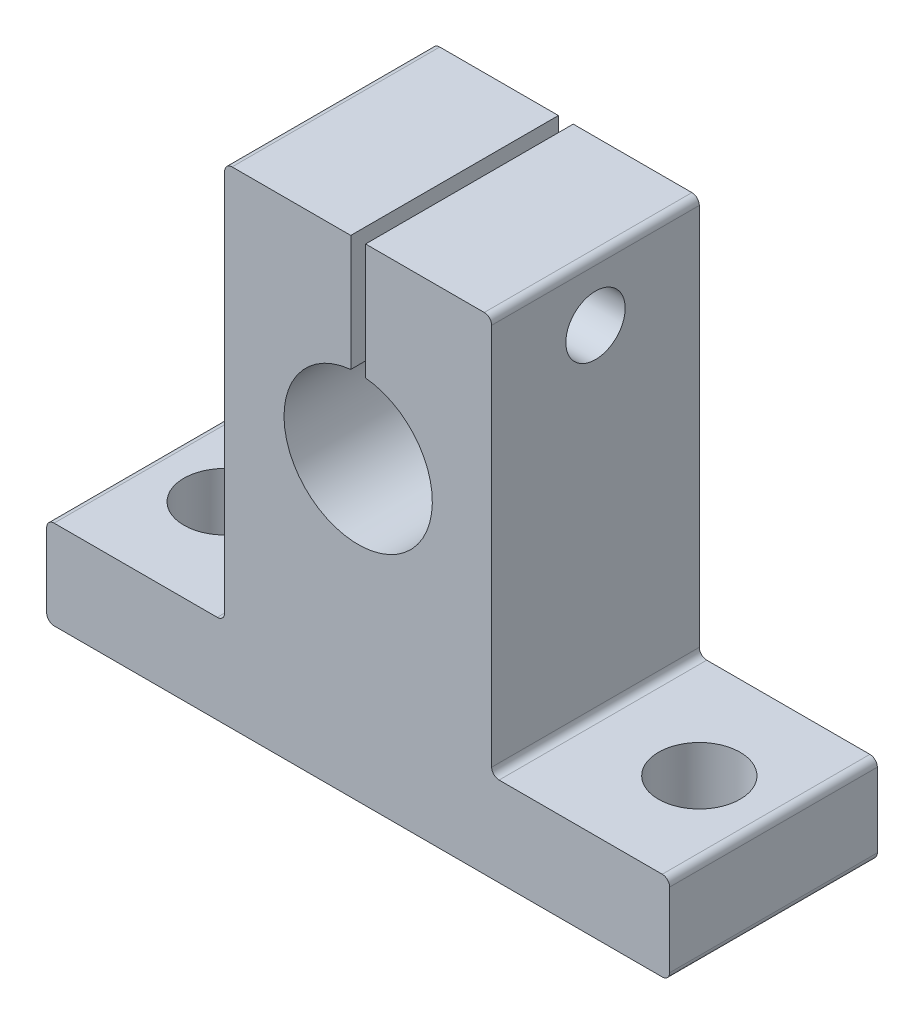
SolidWorks part; units mm, degrees
ref_plane "Front Plane" through (0, 0, 0) normal (0, 0, 1) x (1, 0, 0)
ref_plane "Top Plane" through (0, 0, 0) normal (0, 1, 0) x (1, 0, 0)
ref_plane "Right Plane" through (0, 0, 0) normal (1, 0, 0) x (0, 0, -1)
sketch "Sketch1" plane through (0, 0, 0) normal (0, 0, 1) x (1, 0, 0)
  line L0 (0, 13.4) -> (0, -19.4) construction
  line L1 (-9, -13.4) -> (9, -13.4) construction
  line L2 (-9, -13.4) -> (-9, 13.4)
  line L3 (-9, 13.4) -> (-0.5, 13.4)
  line L4 (9, -13.4) -> (9, 13.4)
  line L5 (-9, -13.4) -> (9, 13.4) construction
  line L6 (-9, 13.4) -> (9, -13.4) construction
  line L7 (-9, -13.4) -> (-21, -13.4)
  line L8 (-21, -13.4) -> (-21, -19.4)
  line L9 (-21, -19.4) -> (21, -19.4)
  line L10 (21, -13.4) -> (21, -19.4)
  line L11 (9, -13.4) -> (21, -13.4)
  line L12 (-0.5, 13.4) -> (-0.5, 5.5749)
  line L13 (0.5, 13.4) -> (0.5, 5.5749)
  line L14 (0.5, 13.4) -> (9, 13.4)
  arc A0 (-0.5, 5.5749) -> (0.5, 5.5749) centre (0, 0.6) ccw
  point P0 (0, 0)
  dimension "D5" = 10
  dimension "D1" = 42
  dimension "D2" = 6
  dimension "D3" = 18
  dimension "D4" = 20
  dimension "D6" = 32.8
  dimension "D7" = 1
extrude "Boss-Extrude1" add sketch "Sketch1" along normal mid plane 14
sketch "Sketch2" plane through (0, 0, 0) normal (0, 1, 0) x (1, 0, 0)
  line L0 (0, 4.443) -> (0, -3.5047) construction
  line L1 (-3.7531, 0) -> (2.9804, 0) construction
  circle A0 centre (-16, 0) radius 2.75
  circle A1 centre (16, 0) radius 2.75
  dimension "D1" = 5.5
  dimension "D2" = 32
extrude "Cut-Extrude1" cut sketch "Sketch2" against normal through all
sketch "Sketch3" plane through (0, 0, 0) normal (1, 0, 0) x (0, 0, -1)
  line L0 (0, 6.3431) -> (0, -7.2672) construction
  line L1 (-7, 13.4) -> (7, 13.4) construction
  circle A0 centre (0, 9.4) radius 2
  dimension "D1" = 4
  dimension "D2" = 4
extrude "Cut-Extrude2" cut sketch "Sketch3" against normal blind 6 and the other way through all
fillet "Fillet1" radius 0.5 8 edges at (21, -19.4, 0) (21, -13.4, 0) (9, -13.4, 0) (-21, -19.4, 0) (-21, -13.4, 0) (-9, -13.4, 0) (-9, 13.4, 0) (9, 13.4, 0)
